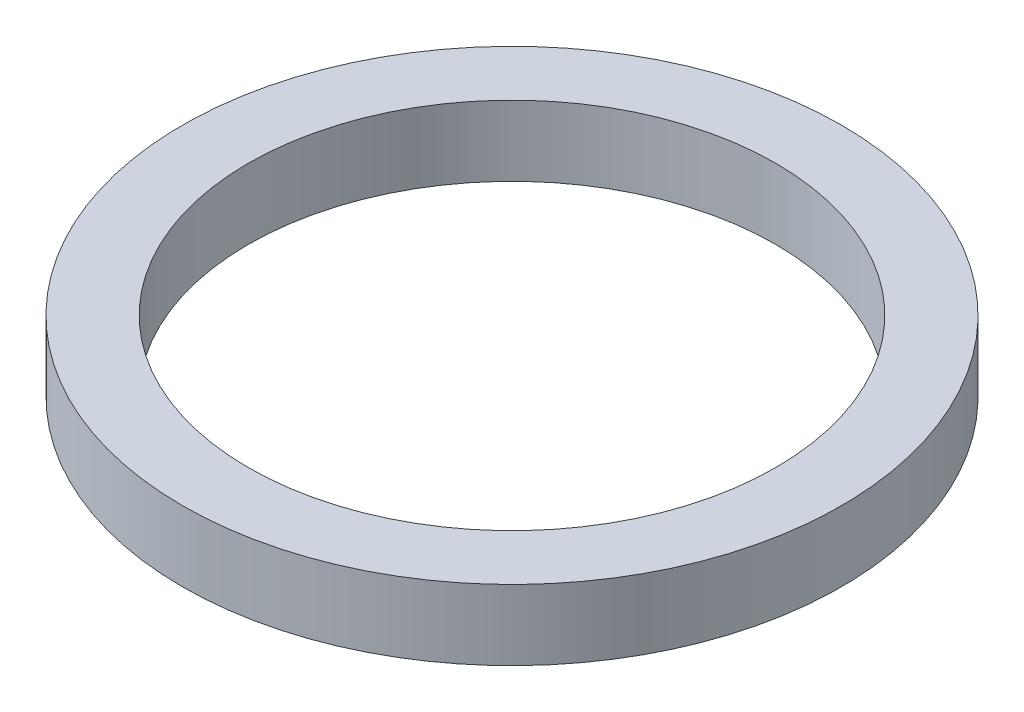
SolidWorks part; units mm, degrees
material "ASTM A36 Steel"
ref_plane "Front Plane" through (0, 0, 0) normal (0, 0, 1) x (1, 0, 0)
ref_plane "Top Plane" through (0, 0, 0) normal (0, 1, 0) x (1, 0, 0)
ref_plane "Right Plane" through (0, 0, 0) normal (1, 0, 0) x (0, 0, -1)
sketch "Sketch1" plane through (0, 0, 0) normal (0, 1, 0) x (1, 0, 0)
  circle A0 centre (0, 0) radius 75
  dimension "D1" = 150
extrude "Boss-Extrude1" add sketch "Sketch1" along normal blind 16
sketch "Sketch2" plane through (0, 0, 0) normal (0, -1, 0) x (1, 0, 0)
  circle A0 centre (0, 0) radius 60
  dimension "D1" = 120
extrude "Cut-Extrude1" cut sketch "Sketch2" against normal up to surface (16 mm away) up to face at (0, 16, 75)
